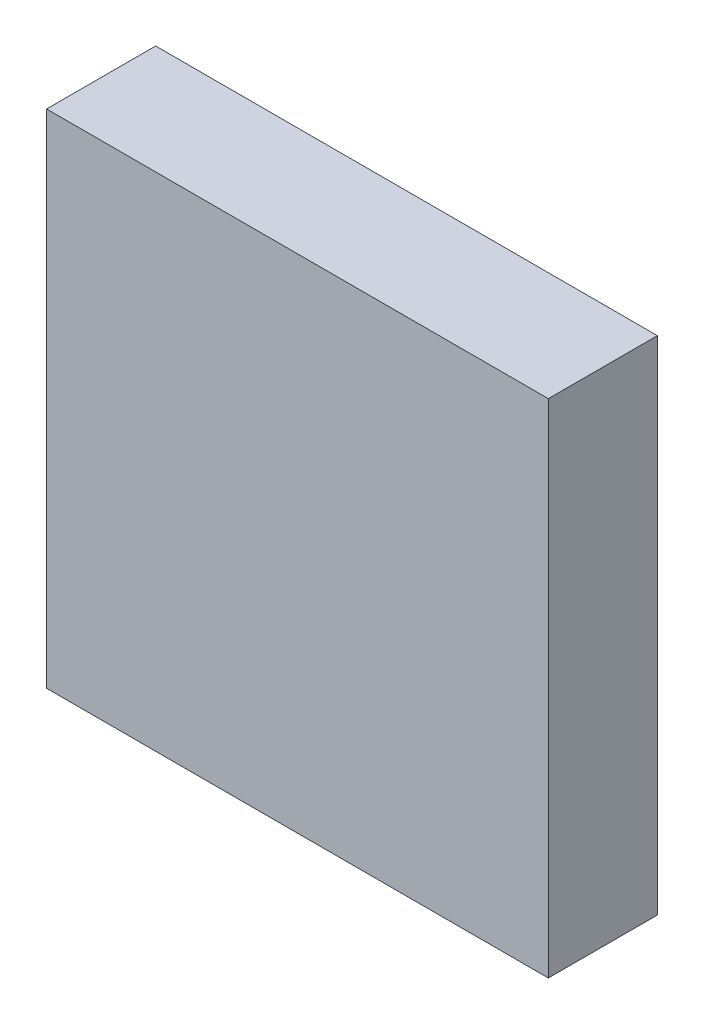
SolidWorks part; units mm, degrees
ref_plane "前视基准面" through (0, 0, 0) normal (0, 0, 1) x (1, 0, 0)
ref_plane "上视基准面" through (0, 0, 0) normal (0, 1, 0) x (1, 0, 0)
ref_plane "右视基准面" through (0, 0, 0) normal (1, 0, 0) x (0, 0, -1)
sketch "草图1" plane through (0, 0, 0) normal (0, 0, 1) x (1, 0, 0)
  line L1 (0, 0) -> (23, 0)
  line L2 (0, 0) -> (0, -23)
  line L3 (0, -23) -> (23, -23)
  line L4 (23, 0) -> (23, -23)
  dimension "D1" = 23
  dimension "D2" = 23
extrude "凸台-拉伸1" add sketch "草图1" along normal blind 5
